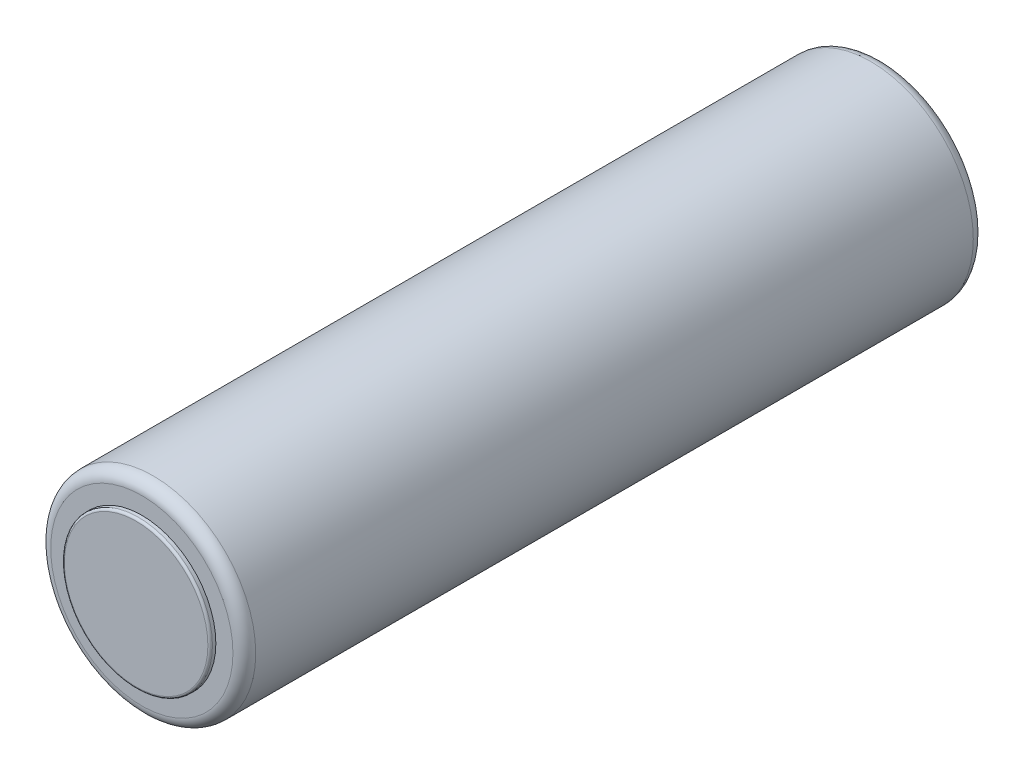
SolidWorks part; units mm, degrees
ref_plane "Спереди" through (0, 0, 0) normal (0, 0, 1) x (1, 0, 0)
ref_plane "Сверху" through (0, 0, 0) normal (0, 1, 0) x (1, 0, 0)
ref_plane "Справа" through (0, 0, 0) normal (1, 0, 0) x (0, 0, -1)
sketch "Эскиз1" plane through (0, 0, 0) normal (0, 0, 1) x (1, 0, 0)
  circle A0 centre (0, 0) radius 9
  dimension "D1" = 18
extrude "Бобышка-Вытянуть1" add sketch "Эскиз1" along normal blind 65
fillet "Скругление1" radius 1 2 edges at (9, 0, 65) (9, 0, 0)
sketch "Эскиз2" plane through (0, 0, 0) normal (0, 0, -1) x (-1, 0, 0)
  circle A0 centre (0, 0) radius 2.5
  dimension "D1" = 5
extrude "Бобышка-Вытянуть2" add sketch "Эскиз2" along normal blind 1 separate body
sketch "Эскиз3" plane through (0, 0, 65) normal (0, 0, 1) x (1, 0, 0)
  circle A0 centre (0, 0) radius 6.5
  dimension "D1" = 13
extrude "Бобышка-Вытянуть3" add sketch "Эскиз3" along normal blind 0.5 separate body
fillet "Скругление2" radius 0.2 1 edges at (-2.5, 0, -1)
fillet "Скругление3" radius 0.2 1 edges at (6.5, 0, 65.5)
